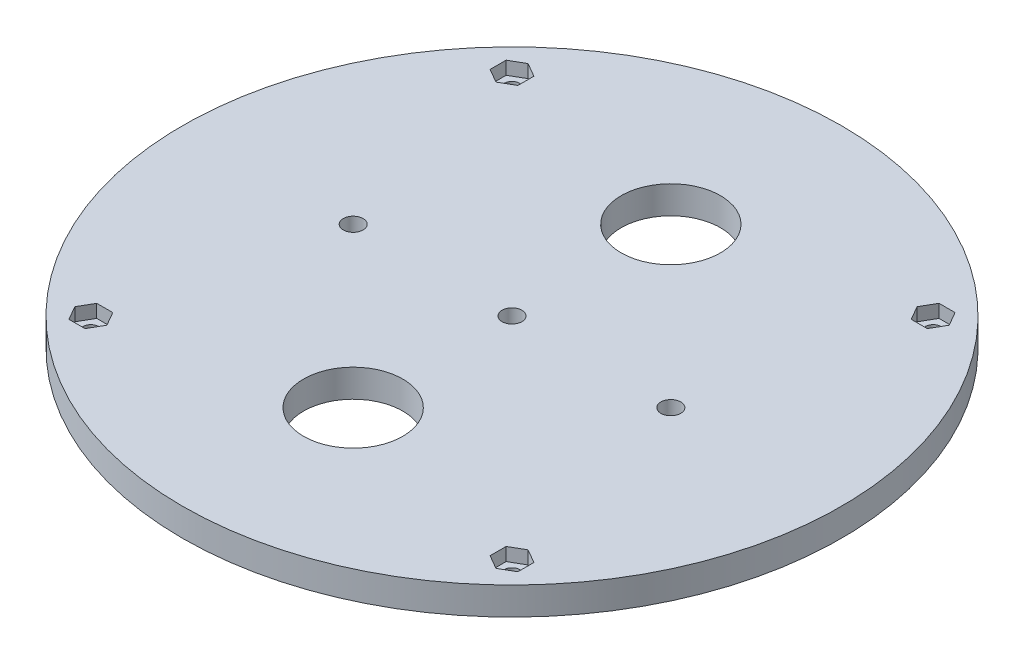
SolidWorks part; units mm, degrees
ref_plane "Front Plane" through (0, 0, 0) normal (0, 0, 1) x (1, 0, 0)
ref_plane "Top Plane" through (0, 0, 0) normal (0, 1, 0) x (1, 0, 0)
ref_plane "Right Plane" through (0, 0, 0) normal (1, 0, 0) x (0, 0, -1)
sketch "Sketch1" plane through (0, 0, 0) normal (0, 1, 0) x (1, 0, 0)
  line L0 (-83, 0) -> (83, 0) construction
  line L1 (0, 83) -> (0, -83) construction
  circle A0 centre (0, 0) radius 83
  circle A2 centre (0, 40) radius 12.5
  circle A3 centre (0, -40) radius 12.5
  dimension "D1" = 166
  dimension "D2" = 25
  dimension "D3" = 25
  dimension "D4" = 40
  dimension "D5" = 40
extrude "Boss-Extrude1" add sketch "Sketch1" along normal blind 7
sketch "Sketch14" plane through (0, 7, 0) normal (0, 1, 0) x (1, 0, 0)
  circle A0 centre (-53.033, 53.033) radius 2
  circle A1 centre (53.033, 53.033) radius 2
  circle A2 centre (53.033, -53.033) radius 2
  circle A3 centre (-53.033, -53.033) radius 2
  point P14 (0, 0)
  dimension "D1" = 75
  dimension "D2" = 4
extrude "Cut-Extrude2" cut sketch "Sketch14" against normal blind 133
sketch "Sketch15" plane through (0, 7, 0) normal (0, 1, 0) x (1, 0, 0)
  line L0 (0, 83) -> (0, -83) construction
  line L1 (-49.533, 55.0537) -> (-53.033, 57.0745)
  line L2 (-53.033, 57.0745) -> (-56.533, 55.0537)
  line L3 (-56.533, 55.0537) -> (-56.533, 51.0123)
  line L4 (-56.533, 51.0123) -> (-53.033, 48.9916)
  line L5 (-53.033, 48.9916) -> (-49.533, 51.0123)
  line L6 (-49.533, 51.0123) -> (-49.533, 55.0537)
  line L7 (55.0537, 49.533) -> (57.0745, 53.033)
  line L8 (57.0745, 53.033) -> (55.0537, 56.533)
  line L9 (55.0537, 56.533) -> (51.0123, 56.533)
  line L10 (51.0123, 56.533) -> (48.9916, 53.033)
  line L11 (48.9916, 53.033) -> (51.0123, 49.533)
  line L12 (51.0123, 49.533) -> (55.0537, 49.533)
  line L13 (49.533, -55.0537) -> (53.033, -57.0745)
  line L14 (53.033, -57.0745) -> (56.533, -55.0537)
  line L15 (56.533, -55.0537) -> (56.533, -51.0123)
  line L16 (56.533, -51.0123) -> (53.033, -48.9916)
  line L17 (53.033, -48.9916) -> (49.533, -51.0123)
  line L18 (49.533, -51.0123) -> (49.533, -55.0537)
  line L19 (-55.0537, -49.533) -> (-57.0745, -53.033)
  line L20 (-57.0745, -53.033) -> (-55.0537, -56.533)
  line L21 (-55.0537, -56.533) -> (-51.0123, -56.533)
  line L22 (-51.0123, -56.533) -> (-48.9916, -53.033)
  line L23 (-48.9916, -53.033) -> (-51.0123, -49.533)
  line L24 (-51.0123, -49.533) -> (-55.0537, -49.533)
  circle A0 centre (-53.033, 53.033) radius 3.5 construction
  point P32 (0, 0)
  dimension "D1" = 7
  dimension "D2" = 4
extrude "Cut-Extrude3" cut sketch "Sketch15" against normal blind 3.3
sketch "Sketch16" plane through (0, 7, 0) normal (0, 1, 0) x (1, 0, 0)
  line L0 (-83, 0) -> (83, 0) construction
  circle A0 centre (-40, 0) radius 2.5
  circle A1 centre (0, 0) radius 2.5
  circle A2 centre (40, 0) radius 2.5
  dimension "D1" = 5
  dimension "D2" = 5
  dimension "D3" = 5
  dimension "D4" = 40
  dimension "D5" = 40
extrude "Cut-Extrude4" cut sketch "Sketch16" against normal blind 10 contours A0 | A2 | A1
